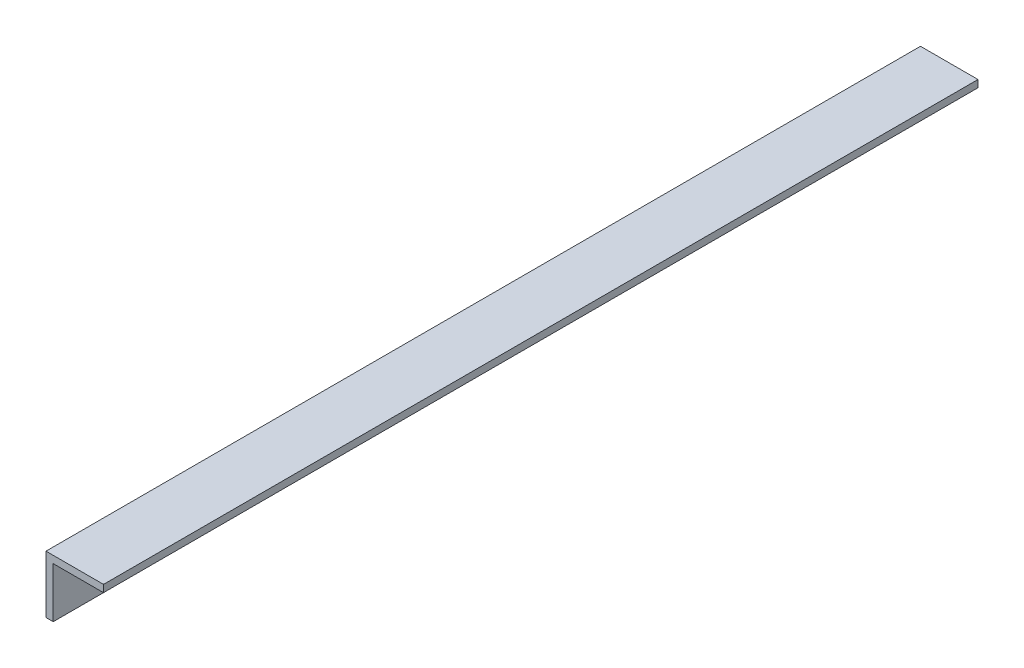
SolidWorks part; units mm, degrees
ref_plane "Front Plane" through (0, 0, 0) normal (0, 0, 1) x (1, 0, 0)
ref_plane "Top Plane" through (0, 0, 0) normal (0, 1, 0) x (1, 0, 0)
ref_plane "Right Plane" through (0, 0, 0) normal (1, 0, 0) x (0, 0, -1)
sketch "Sketch1" plane through (0, 0, 0) normal (0, 0, 1) x (1, 0, 0)
  line L0 (0, 0) -> (0, 25.4)
  line L1 (0, 25.4) -> (25.4, 25.4)
  line L2 (25.4, 25.4) -> (25.4, 22.225)
  line L3 (25.4, 22.225) -> (3.175, 22.225)
  line L4 (3.175, 22.225) -> (3.175, 0)
  line L5 (3.175, 0) -> (0, 0)
  dimension "D1" = 25.4
  dimension "D2" = 25.4
  dimension "D3" = 3.175
  dimension "D4" = 3.175
extrude "Boss-Extrude1" add sketch "Sketch1" along normal blind 386.08
sketch "Sketch2" plane through (3.175, 0, 0) normal (1, 0, 0) x (0, 0, -1)
  line L0 (-386.08, 25.4) -> (0, 25.4) construction
  line L1 (-386.08, 0) -> (-386.08, 22.225) construction
  circle A0 centre (-367.03, 12.7) radius 3.9688
  circle A1 centre (-227.33, 12.7) radius 3.9688
  dimension "D1" = 12.7
  dimension "D3" = 139.7
  dimension "D2" = 19.05
  dimension "D4" = 12.7
extrude "Cut-Extrude1" cut sketch "Sketch2" against normal blind 6.35
